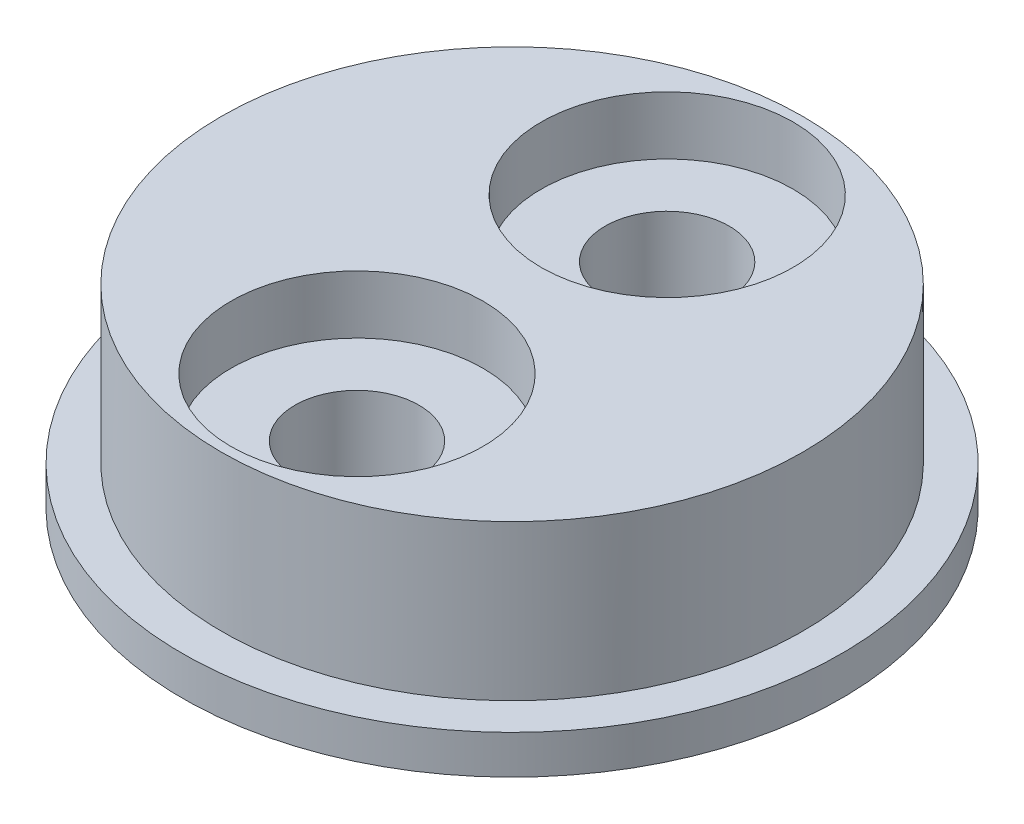
SolidWorks part; units mm, degrees
ref_plane "Front Plane" through (0, 0, 0) normal (0, 0, 1) x (1, 0, 0)
ref_plane "Top Plane" through (0, 0, 0) normal (0, 1, 0) x (1, 0, 0)
ref_plane "Right Plane" through (0, 0, 0) normal (1, 0, 0) x (0, 0, -1)
sketch "Sketch1" plane through (0, 0, 0) normal (0, 1, 0) x (1, 0, 0)
  circle A0 centre (0, 0) radius 7.5
  dimension "D1" = 15
extrude "Boss-Extrude1" add sketch "Sketch1" along normal blind 5
sketch "Sketch2" plane through (0, 5, 0) normal (0, 1, 0) x (1, 0, 0)
  line L0 (0, 7.9744) -> (0, -8.0985) construction
  circle A2 centre (0, 0) radius 4 construction
  circle A3 centre (0, 4) radius 3.25
  circle A4 centre (0, -4) radius 3.25
  point P12 (0, 0)
  dimension "D1" = 8
  dimension "D2" = 6.5
  dimension "D3" = 2
extrude "Cut-Extrude1" cut sketch "Sketch2" against normal blind 1.5
sketch "Sketch4" plane through (0, 0, 0) normal (0, -1, 0) x (1, 0, 0)
  circle A0 centre (0, 0) radius 8.5
  dimension "D1" = 17
extrude "Boss-Extrude2" add sketch "Sketch4" against normal blind 1
sketch "Sketch3" plane through (0, 5, 0) normal (0, 1, 0) x (1, 0, 0)
  line L0 (0, 8.0571) -> (0, -8.4294) construction
  circle A0 centre (0, 4) radius 1.6
  circle A1 centre (0, -4) radius 1.6
  circle A2 centre (0, 0) radius 4 construction
  dimension "D1" = 8
  dimension "D2" = 3.2
extrude "Cut-Extrude2" cut sketch "Sketch3" against normal through all
